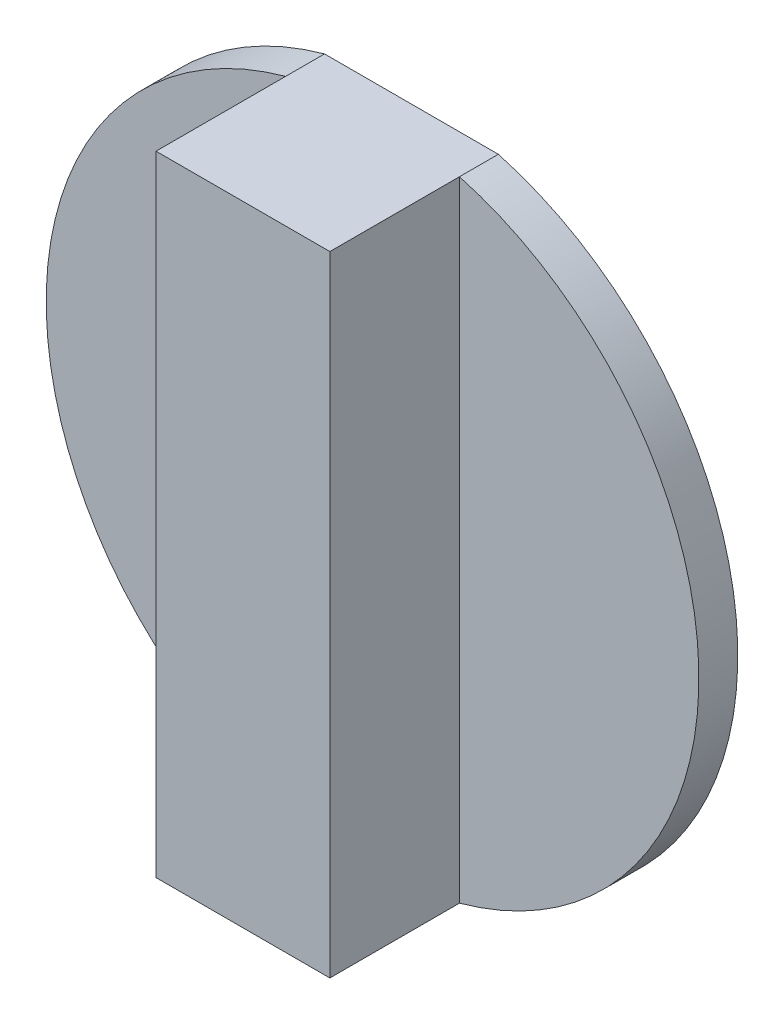
SolidWorks part; units mm, degrees
ref_plane "Front Plane" through (0, 0, 0) normal (0, 0, 1) x (1, 0, 0)
ref_plane "Top Plane" through (0, 0, 0) normal (0, 1, 0) x (1, 0, 0)
ref_plane "Right Plane" through (0, 0, 0) normal (1, 0, 0) x (0, 0, -1)
sketch "Sketch1" plane through (0, 0, 0) normal (0, 0, 1) x (1, 0, 0)
  line L8 (-3.2215, 139.4927) -> (10.1902, 139.4927)
  line L11 (-3.2215, 139.4927) -> (-3.2215, 90.9541)
  line L12 (10.1902, 90.9541) -> (10.1902, 139.4927)
  line L13 (-3.2215, 90.9541) -> (10.1902, 90.9541)
  circle A1 centre (3.4844, 115.2234) radius 25.1787
  point P7 (5.7785, 90.2234)
  point P10 (5.7785, 140.2234)
extrude "Boss-Extrude4" add sketch "Sketch1" along normal blind 3 contours L11 A1 | L12 A1 | L12 A1 L11
ref_plane "Plane1" through (0, 0, 3) normal (0, 0, 1) x (1, 0, 0)
sketch "Sketch2" plane through (0, 0, 3) normal (0, 0, 1) x (1, 0, 0)
  line L0 (-3.2215, 139.4927) -> (10.1902, 139.4927)
  line L1 (10.1902, 139.4927) -> (10.1902, 90.9541)
  line L2 (10.1902, 90.9541) -> (-3.2215, 90.9541)
  line L3 (-3.2215, 90.9541) -> (-3.2215, 139.4927)
extrude "Boss-Extrude5" add sketch "Sketch2" along normal blind 10
